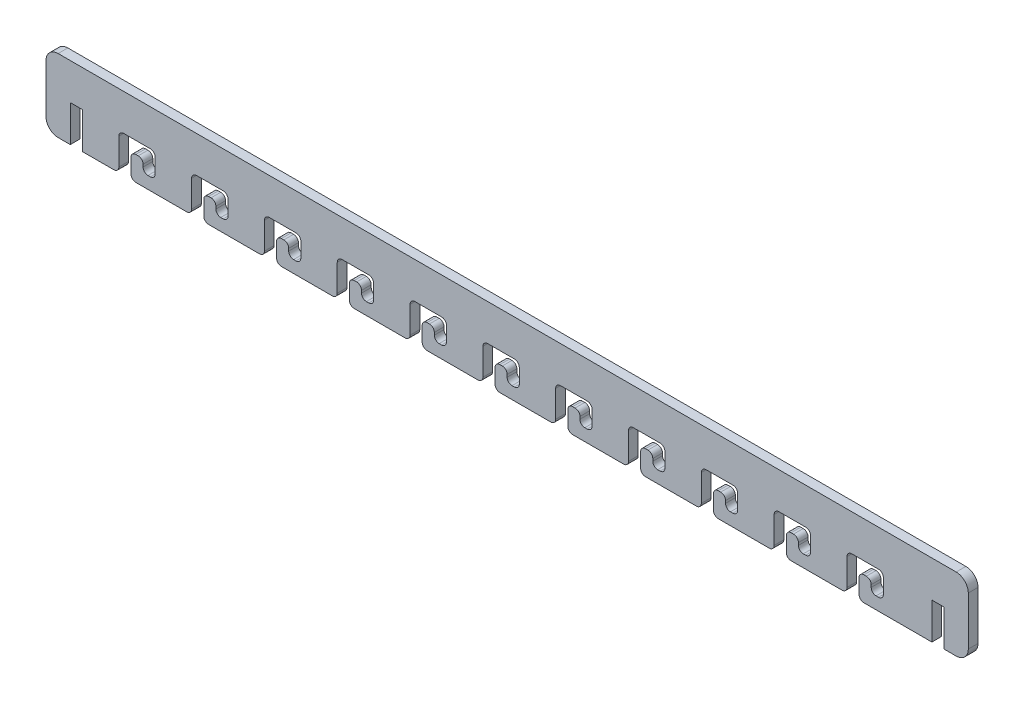
SolidWorks part; units mm, degrees
ref_plane "Front Plane" through (0, 0, 0) normal (0, 0, 1) x (1, 0, 0)
ref_plane "Top Plane" through (0, 0, 0) normal (0, 1, 0) x (1, 0, 0)
ref_plane "Right Plane" through (0, 0, 0) normal (1, 0, 0) x (0, 0, -1)
sketch "Sketch1" plane through (0, 0, 0) normal (0, 0, 1) x (1, 0, 0)
  line L0 (190, 0) -> (190, -52.5585) construction
  line L1 (5, 0) -> (10, 0)
  line L2 (0, 5) -> (0, 25)
  line L3 (5, 30) -> (375, 30)
  line L4 (380, 5) -> (380, 25)
  line L5 (30, 2) -> (30, 13)
  line L6 (10, 0) -> (10, 15)
  line L7 (10, 15) -> (15, 15)
  line L8 (15, 0) -> (15, 15)
  line L9 (365, 0) -> (365, 15)
  line L10 (370, 15) -> (365, 15)
  line L11 (370, 0) -> (370, 15)
  line L12 (15, 0) -> (28, 0)
  line L13 (370, 0) -> (375, 0)
  line L14 (32, 15) -> (43, 15)
  line L15 (45, 13) -> (45, 7)
  line L16 (43, 5) -> (42, 5)
  line L17 (40, 7) -> (40, 8)
  line L18 (38, 10) -> (37, 10)
  line L19 (35, 8) -> (35, 2)
  line L20 (37, 0) -> (58, 0)
  line L21 (60, 2) -> (60, 13)
  line L22 (62, 15) -> (73, 15)
  line L23 (75, 13) -> (75, 7)
  line L24 (73, 5) -> (72, 5)
  line L25 (70, 7) -> (70, 8)
  line L26 (68, 10) -> (67, 10)
  line L27 (65, 8) -> (65, 2)
  line L28 (90, 2) -> (90, 13)
  line L29 (92, 15) -> (103, 15)
  line L30 (105, 13) -> (105, 7)
  line L31 (103, 5) -> (102, 5)
  line L32 (100, 7) -> (100, 8)
  line L33 (98, 10) -> (97, 10)
  line L34 (95, 8) -> (95, 2)
  line L35 (120, 2) -> (120, 13)
  line L36 (122, 15) -> (133, 15)
  line L37 (135, 13) -> (135, 7)
  line L38 (133, 5) -> (132, 5)
  line L39 (130, 7) -> (130, 8)
  line L40 (128, 10) -> (127, 10)
  line L41 (125, 8) -> (125, 2)
  line L42 (150, 2) -> (150, 13)
  line L43 (152, 15) -> (163, 15)
  line L44 (165, 13) -> (165, 7)
  line L45 (163, 5) -> (162, 5)
  line L46 (160, 7) -> (160, 8)
  line L47 (158, 10) -> (157, 10)
  line L48 (155, 8) -> (155, 2)
  line L49 (180, 2) -> (180, 13)
  line L50 (182, 15) -> (193, 15)
  line L51 (195, 13) -> (195, 7)
  line L52 (193, 5) -> (192, 5)
  line L53 (190, 7) -> (190, 8)
  line L54 (188, 10) -> (187, 10)
  line L55 (185, 8) -> (185, 2)
  line L56 (210, 2) -> (210, 13)
  line L57 (212, 15) -> (223, 15)
  line L58 (225, 13) -> (225, 7)
  line L59 (223, 5) -> (222, 5)
  line L60 (220, 7) -> (220, 8)
  line L61 (218, 10) -> (217, 10)
  line L62 (215, 8) -> (215, 2)
  line L63 (240, 2) -> (240, 13)
  line L64 (242, 15) -> (253, 15)
  line L65 (255, 13) -> (255, 7)
  line L66 (253, 5) -> (252, 5)
  line L67 (250, 7) -> (250, 8)
  line L68 (248, 10) -> (247, 10)
  line L69 (245, 8) -> (245, 2)
  line L70 (270, 2) -> (270, 13)
  line L71 (272, 15) -> (283, 15)
  line L72 (285, 13) -> (285, 7)
  line L73 (283, 5) -> (282, 5)
  line L74 (280, 7) -> (280, 8)
  line L75 (278, 10) -> (277, 10)
  line L76 (275, 8) -> (275, 2)
  line L77 (300, 2) -> (300, 13)
  line L78 (302, 15) -> (313, 15)
  line L79 (315, 13) -> (315, 7)
  line L80 (313, 5) -> (312, 5)
  line L81 (310, 7) -> (310, 8)
  line L82 (308, 10) -> (307, 10)
  line L83 (305, 8) -> (305, 2)
  line L84 (330, 2) -> (330, 13)
  line L85 (332, 15) -> (343, 15)
  line L86 (345, 13) -> (345, 7)
  line L87 (343, 5) -> (342, 5)
  line L88 (340, 7) -> (340, 8)
  line L89 (338, 10) -> (337, 10)
  line L90 (335, 8) -> (335, 2)
  line L91 (67, 0) -> (88, 0)
  line L92 (97, 0) -> (118, 0)
  line L93 (127, 0) -> (148, 0)
  line L94 (157, 0) -> (178, 0)
  line L95 (187, 0) -> (208, 0)
  line L96 (217, 0) -> (238, 0)
  line L97 (247, 0) -> (268, 0)
  line L98 (277, 0) -> (298, 0)
  line L99 (307, 0) -> (328, 0)
  line L100 (337, 0) -> (365, 0)
  arc A0 (5, 0) -> (0, 5) centre (5, 5) cw
  arc A1 (0, 25) -> (5, 30) centre (5, 25) cw
  arc A2 (375, 0) -> (380, 5) centre (375, 5) ccw
  arc A3 (375, 30) -> (380, 25) centre (375, 25) cw
  arc A4 (37, 10) -> (35, 8) centre (37, 8) ccw
  arc A5 (40, 8) -> (38, 10) centre (38, 8) ccw
  arc A6 (42, 5) -> (40, 7) centre (42, 7) cw
  arc A7 (45, 7) -> (43, 5) centre (43, 7) cw
  arc A8 (43, 15) -> (45, 13) centre (43, 13) cw
  arc A9 (30, 13) -> (32, 15) centre (32, 13) cw
  arc A10 (35, 2) -> (37, 0) centre (37, 2) ccw
  arc A11 (30, 2) -> (28, 0) centre (28, 2) cw
  arc A12 (60, 2) -> (58, 0) centre (58, 2) cw
  arc A13 (60, 13) -> (62, 15) centre (62, 13) cw
  arc A14 (73, 15) -> (75, 13) centre (73, 13) cw
  arc A15 (75, 7) -> (73, 5) centre (73, 7) cw
  arc A16 (72, 5) -> (70, 7) centre (72, 7) cw
  arc A17 (70, 8) -> (68, 10) centre (68, 8) ccw
  arc A18 (67, 10) -> (65, 8) centre (67, 8) ccw
  arc A19 (65, 2) -> (67, 0) centre (67, 2) ccw
  arc A20 (90, 2) -> (88, 0) centre (88, 2) cw
  arc A21 (90, 13) -> (92, 15) centre (92, 13) cw
  arc A22 (103, 15) -> (105, 13) centre (103, 13) cw
  arc A23 (105, 7) -> (103, 5) centre (103, 7) cw
  arc A24 (102, 5) -> (100, 7) centre (102, 7) cw
  arc A25 (100, 8) -> (98, 10) centre (98, 8) ccw
  arc A26 (97, 10) -> (95, 8) centre (97, 8) ccw
  arc A27 (95, 2) -> (97, 0) centre (97, 2) ccw
  arc A28 (120, 2) -> (118, 0) centre (118, 2) cw
  arc A29 (120, 13) -> (122, 15) centre (122, 13) cw
  arc A30 (133, 15) -> (135, 13) centre (133, 13) cw
  arc A31 (135, 7) -> (133, 5) centre (133, 7) cw
  arc A32 (132, 5) -> (130, 7) centre (132, 7) cw
  arc A33 (130, 8) -> (128, 10) centre (128, 8) ccw
  arc A34 (127, 10) -> (125, 8) centre (127, 8) ccw
  arc A35 (125, 2) -> (127, 0) centre (127, 2) ccw
  arc A36 (150, 2) -> (148, 0) centre (148, 2) cw
  arc A37 (150, 13) -> (152, 15) centre (152, 13) cw
  arc A38 (163, 15) -> (165, 13) centre (163, 13) cw
  arc A39 (165, 7) -> (163, 5) centre (163, 7) cw
  arc A40 (162, 5) -> (160, 7) centre (162, 7) cw
  arc A41 (160, 8) -> (158, 10) centre (158, 8) ccw
  arc A42 (157, 10) -> (155, 8) centre (157, 8) ccw
  arc A43 (155, 2) -> (157, 0) centre (157, 2) ccw
  arc A44 (180, 2) -> (178, 0) centre (178, 2) cw
  arc A45 (180, 13) -> (182, 15) centre (182, 13) cw
  arc A46 (193, 15) -> (195, 13) centre (193, 13) cw
  arc A47 (195, 7) -> (193, 5) centre (193, 7) cw
  arc A48 (192, 5) -> (190, 7) centre (192, 7) cw
  arc A49 (190, 8) -> (188, 10) centre (188, 8) ccw
  arc A50 (187, 10) -> (185, 8) centre (187, 8) ccw
  arc A51 (185, 2) -> (187, 0) centre (187, 2) ccw
  arc A52 (210, 2) -> (208, 0) centre (208, 2) cw
  arc A53 (210, 13) -> (212, 15) centre (212, 13) cw
  arc A54 (223, 15) -> (225, 13) centre (223, 13) cw
  arc A55 (225, 7) -> (223, 5) centre (223, 7) cw
  arc A56 (222, 5) -> (220, 7) centre (222, 7) cw
  arc A57 (220, 8) -> (218, 10) centre (218, 8) ccw
  arc A58 (217, 10) -> (215, 8) centre (217, 8) ccw
  arc A59 (215, 2) -> (217, 0) centre (217, 2) ccw
  arc A60 (240, 2) -> (238, 0) centre (238, 2) cw
  arc A61 (240, 13) -> (242, 15) centre (242, 13) cw
  arc A62 (253, 15) -> (255, 13) centre (253, 13) cw
  arc A63 (255, 7) -> (253, 5) centre (253, 7) cw
  arc A64 (252, 5) -> (250, 7) centre (252, 7) cw
  arc A65 (250, 8) -> (248, 10) centre (248, 8) ccw
  arc A66 (247, 10) -> (245, 8) centre (247, 8) ccw
  arc A67 (245, 2) -> (247, 0) centre (247, 2) ccw
  arc A68 (270, 2) -> (268, 0) centre (268, 2) cw
  arc A69 (270, 13) -> (272, 15) centre (272, 13) cw
  arc A70 (283, 15) -> (285, 13) centre (283, 13) cw
  arc A71 (285, 7) -> (283, 5) centre (283, 7) cw
  arc A72 (282, 5) -> (280, 7) centre (282, 7) cw
  arc A73 (280, 8) -> (278, 10) centre (278, 8) ccw
  arc A74 (277, 10) -> (275, 8) centre (277, 8) ccw
  arc A75 (275, 2) -> (277, 0) centre (277, 2) ccw
  arc A76 (300, 2) -> (298, 0) centre (298, 2) cw
  arc A77 (300, 13) -> (302, 15) centre (302, 13) cw
  arc A78 (313, 15) -> (315, 13) centre (313, 13) cw
  arc A79 (315, 7) -> (313, 5) centre (313, 7) cw
  arc A80 (312, 5) -> (310, 7) centre (312, 7) cw
  arc A81 (310, 8) -> (308, 10) centre (308, 8) ccw
  arc A82 (307, 10) -> (305, 8) centre (307, 8) ccw
  arc A83 (305, 2) -> (307, 0) centre (307, 2) ccw
  arc A84 (330, 2) -> (328, 0) centre (328, 2) cw
  arc A85 (330, 13) -> (332, 15) centre (332, 13) cw
  arc A86 (343, 15) -> (345, 13) centre (343, 13) cw
  arc A87 (345, 7) -> (343, 5) centre (343, 7) cw
  arc A88 (342, 5) -> (340, 7) centre (342, 7) cw
  arc A89 (340, 8) -> (338, 10) centre (338, 8) ccw
  arc A90 (337, 10) -> (335, 8) centre (337, 8) ccw
  arc A91 (335, 2) -> (337, 0) centre (337, 2) ccw
  point P17 (0, 0)
  point P20 (0, 30)
  point P25 (380, 30)
  point P36 (35, 10)
  point P39 (40, 10)
  point P42 (40, 5)
  point P45 (45, 5)
  point P52 (35, 0)
  dimension "D6" = 5
  dimension "D14" = 2
  dimension "D15" = 2
  dimension "D1" = 380
  dimension "D2" = 10
  dimension "D3" = 5
  dimension "D4" = 15
  dimension "D5" = 30
  dimension "D7" = 5
  dimension "D8" = 5
  dimension "D9" = 5
  dimension "D10" = 5
  dimension "D11" = 5
  dimension "D12" = 5
  dimension "D13" = 15
  dimension "D16" = 11
extrude "Boss-Extrude1" add sketch "Sketch1" along normal blind 4
